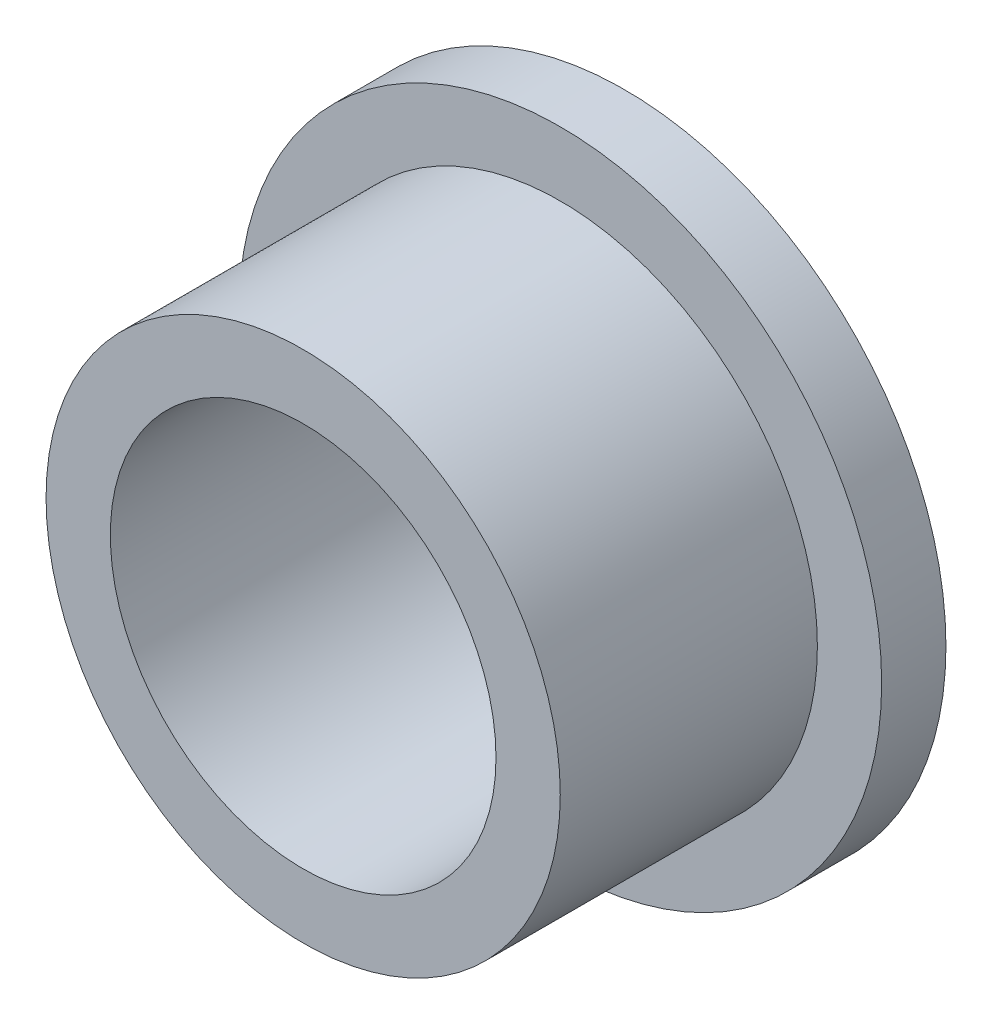
SolidWorks part; units mm, degrees
ref_plane "正面" through (0, 0, 0) normal (0, 0, 1) x (1, 0, 0)
ref_plane "平面" through (0, 0, 0) normal (0, 1, 0) x (1, 0, 0)
ref_plane "右側面" through (0, 0, 0) normal (1, 0, 0) x (0, 0, -1)
sketch "ｽｹｯﾁ1" plane through (0, 0, 0) normal (0, 0, 1) x (1, 0, 0)
  circle A0 centre (0, 0) radius 5
  circle A1 centre (0, 0) radius 3
  dimension "D1" = 6
  dimension "D2" = 10
extrude "ﾎﾞｽ - 押し出し1" add sketch "ｽｹｯﾁ1" along normal blind 1
sketch "ｽｹｯﾁ2" plane through (0, 0, 0) normal (0, 0, 1) x (1, 0, 0)
  circle A0 centre (0, 0) radius 3
  circle A1 centre (0, 0) radius 4
  dimension "D1" = 8
  dimension "D2" = 6
extrude "ﾎﾞｽ - 押し出し2" add sketch "ｽｹｯﾁ2" along normal blind 5
